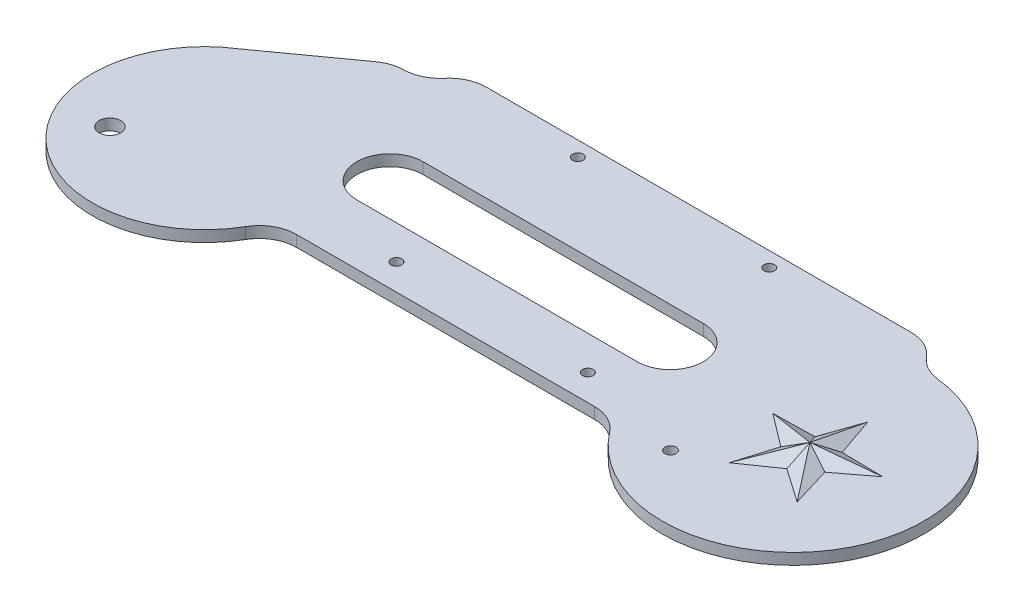
SolidWorks part; units mm, degrees
ref_plane "Front Plane" through (0, 0, 0) normal (0, 0, 1) x (1, 0, 0)
ref_plane "Top Plane" through (0, 0, 0) normal (0, 1, 0) x (1, 0, 0)
ref_plane "Right Plane" through (0, 0, 0) normal (1, 0, 0) x (0, 0, -1)
sketch "Sketch1" plane through (0, 0, 0) normal (0, 1, 0) x (1, 0, 0)
  line L0 (67.5, -35) -> (-117.9377, -35) construction
  line L1 (-97.8109, -17.5) -> (97.8109, -17.5)
  line L2 (-97.8109, -17.5) -> (-97.8109, 17.5)
  line L3 (-97.8109, 17.5) -> (97.8109, 17.5)
  line L4 (97.8109, -17.5) -> (97.8109, 17.5)
  line L5 (-97.8109, -17.5) -> (97.8109, 17.5) construction
  line L6 (-97.8109, 17.5) -> (97.8109, -17.5) construction
  line L7 (67.5, 35) -> (-74.7137, 35)
  line L8 (-74.7137, 35) -> (-98.4239, 17.925)
  line L9 (-61.4217, 42.0312) -> (61.882, 42.0312)
  line L10 (-61.4217, 42.0312) -> (-61.4217, 35)
  line L11 (61.882, 42.0312) -> (61.882, 35)
  line L12 (-61.4217, 42.0312) -> (-67.0397, 35)
  line L13 (61.882, 42.0312) -> (67.5, 35)
  line L14 (35.422, -14) -> (-53.2126, -14)
  circle A0 centre (-82.5, -7.5) radius 30
  circle A1 centre (67.5, 0) radius 35
  circle A2 centre (-97.8109, -17.5) radius 2.875
  circle A3 centre (52.1891, -17.5) radius 1.5
  point P6 (0, 0)
  dimension "D3" = 27.5
  dimension "D6" = 0
  dimension "D1" = 60
  dimension "D2" = 70
  dimension "D8" = 5.75
  dimension "D9" = 3
  dimension "D4" = 67.5
  dimension "D5" = 150
  dimension "D7" = 35
  dimension "D10" = 150
  dimension "D11" = 9
  dimension "D12" = 9
  dimension "D13" = 3.5
  dimension "D14" = 0
extrude "Boss-Extrude1" add sketch "Sketch1" along normal blind 3 contours L11 L9 L10 L7 | A1 L7 L8 A0 L3 | L3 A0 | A2 L1 A0 L3 L2 | A2 L1 A0 | A1 L3 A0 L1 | A3 L1 L4 L3 A1 | A1 L3 | L4 A1 | L13 L11 L7 | L10 L12 L7 | A0 L3 L8
sketch "Sketch2" plane through (0, 3, 0) normal (0, 1, 0) x (1, 0, 0)
  line L0 (-47.8109, 7.4406) -> (27.1891, 7.4406) construction
  line L1 (-47.8109, 16.2943) -> (27.1891, 16.2943)
  line L2 (-47.8109, -1.413) -> (27.1891, -1.413)
  arc A0 (-47.8109, 16.2943) -> (-47.8109, -1.413) centre (-47.8109, 7.4406) ccw
  arc A1 (27.1891, -1.413) -> (27.1891, 16.2943) centre (27.1891, 7.4406) ccw
  circle A2 centre (-97.8109, -17.5) radius 2.875 construction
  point P2 (-10.3109, 7.4406)
  dimension "D1" = 75
  dimension "D2" = 50
extrude "Cut-Extrude1" cut sketch "Sketch2" against normal blind 10
sketch "Sketch3" plane through (0, 3, 0) normal (0, 1, 0) x (1, 0, 0)
  line L1 (-61.4217, 42.0312) -> (61.882, 42.0312) construction
  circle A0 centre (-28.1428, -10.5) radius 1.42
  circle A1 centre (23.0886, -10.5) radius 1.42
  circle A2 centre (-28.1428, 38.0312) radius 1.42
  circle A3 centre (23.0886, 38.0312) radius 1.42
  dimension "D3" = 2.84
  dimension "D4" = 2.84
  dimension "D5" = 2.84
  dimension "D6" = 2.84
  dimension "D7" = 4
  dimension "D8" = 4
extrude "Cut-Extrude2" cut sketch "Sketch3" against normal blind 20
sketch "Sketch5" plane through (0, 3, 0) normal (0, 1, 0) x (1, 0, 0)
  line L0 (-97.8109, -17.5) -> (-97.8109, -7.6754) construction
  circle A0 centre (-97.8109, -11.15) radius 1.42
  circle A1 centre (-97.8109, -17.5) radius 2.75
  circle A2 centre (-91.5998, -18.8208) radius 1.42
  circle A3 centre (-91.4609, -17.5) radius 1.42
  circle A4 centre (-91.4609, -17.5) radius 1.42
  dimension "D1" = 2.84
  dimension "D3" = 2.84
  dimension "D4" = 2.84
  dimension "D5" = 2.84
  dimension "D2" = 6.35
  dimension "D6" = 6.35
  dimension "D7" = 6.35
  dimension "D8" = 6.35
extrude "Cut-Extrude3" [suppressed] cut sketch "Sketch5" against normal blind 10
sketch "Sketch6" plane through (0, 3, 0) normal (0, 1, 0) x (1, 0, 0)
  line L0 (72, 0) -> (72, 17.3137) construction
  line L1 (72, 15.4508) -> (57.3054, 4.7746)
  line L2 (57.3054, 4.7746) -> (62.9182, -12.5)
  line L3 (62.9182, -12.5) -> (81.0818, -12.5)
  line L4 (81.0818, -12.5) -> (86.6946, 4.7746)
  line L5 (86.6946, 4.7746) -> (72, 15.4508)
  line L6 (72, -6.1803) -> (77.8779, -1.9098)
  line L7 (77.8779, -1.9098) -> (75.6327, 5)
  line L8 (75.6327, 5) -> (68.3673, 5)
  line L9 (68.3673, 5) -> (66.1221, -1.9098)
  line L10 (66.1221, -1.9098) -> (72, -6.1803)
  line L11 (72, 0) -> (75.6327, 5) construction
  line L12 (72, 15.4508) -> (75.6327, 5)
  line L13 (86.6946, 4.7746) -> (75.6327, 5)
  line L14 (86.6946, 4.7746) -> (77.8779, -1.9098)
  line L15 (81.0818, -12.5) -> (77.8779, -1.9098)
  line L16 (72, -6.1803) -> (81.0818, -12.5)
  line L17 (72, -6.1803) -> (62.9182, -12.5)
  line L18 (66.1221, -1.9098) -> (62.9182, -12.5)
  line L19 (66.1221, -1.9098) -> (57.3054, 4.7746)
  line L20 (68.3673, 5) -> (57.3054, 4.7746)
  line L21 (68.3673, 5) -> (72, 15.4508)
  circle A0 centre (72, 0) radius 12.5 construction
  circle A1 centre (72, 0) radius 5 construction
  dimension "D2" = 10
  dimension "D3" = 25
  dimension "D1" = 36
  dimension "D4" = 72
ref_plane "Plane1" through (0, 6, 0) normal (0, 1, 0) x (1, 0, 0)
sketch "Sketch7" plane through (0, 6, 0) normal (0, 1, 0) x (1, 0, 0)
  point P0 (72, 0)
  dimension "D1" = 72
loft "Loft1" add profiles "Sketch7" section "Sketch7" section "Sketch6"
fillet "Fillet3" radius 10 2 edges at (37.1891, 1.5, 17.5) (-54.2157, 1.5, 17.5)
fillet "Fillet5" radius 10 2 edges at (67.5, 1.5, -35) (-67.0397, 1.5, -35)
fillet "Fillet6" radius 10 3 edges at (61.882, 1.5, -42.0312) (-61.4217, 1.5, -42.0312) (-74.7137, 1.5, -35)
